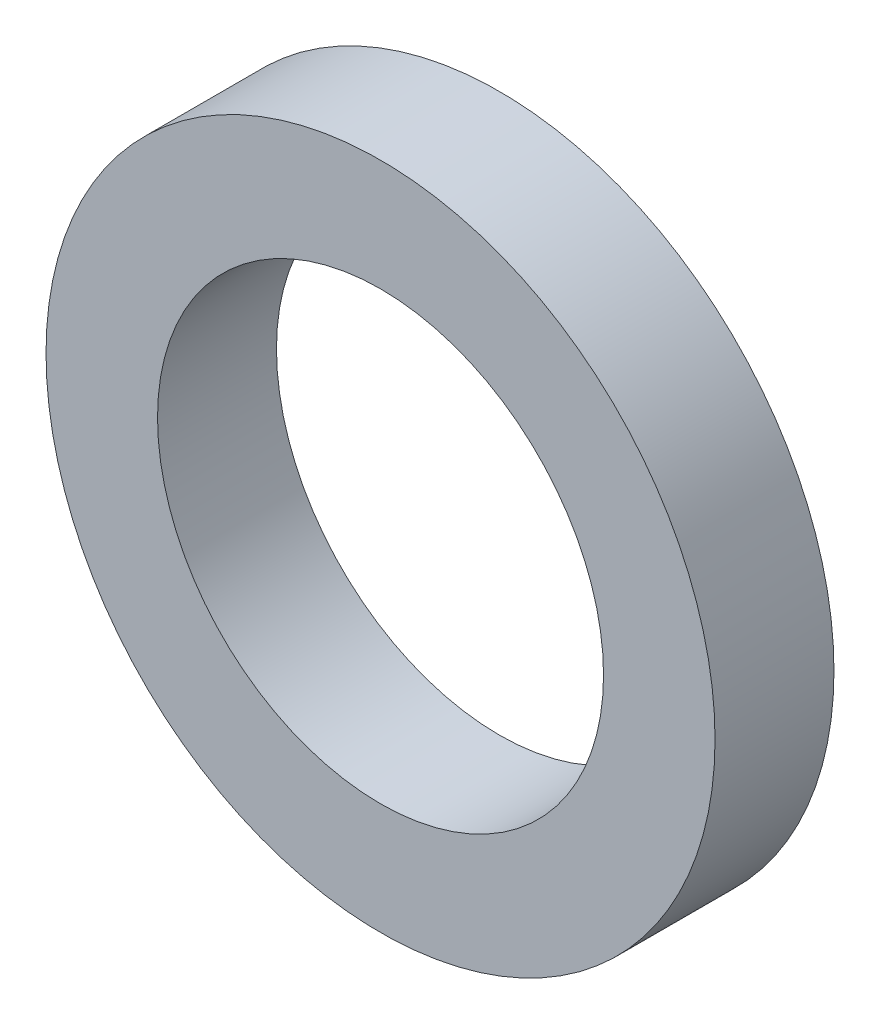
SolidWorks part; units mm, degrees
ref_plane "Front" through (0, 0, 0) normal (0, 0, 1) x (1, 0, 0)
ref_plane "Top" through (0, 0, 0) normal (0, 1, 0) x (1, 0, 0)
ref_plane "Right" through (0, 0, 0) normal (1, 0, 0) x (0, 0, -1)
sketch "Sketch1" plane through (0, 0, 0) normal (0, 0, 1) x (1, 0, 0)
  circle A0 centre (0, 0) radius 6
  circle A1 centre (0, 0) radius 9
extrude "Boss-Extrude1" add sketch "Sketch1" along normal blind 3.2
